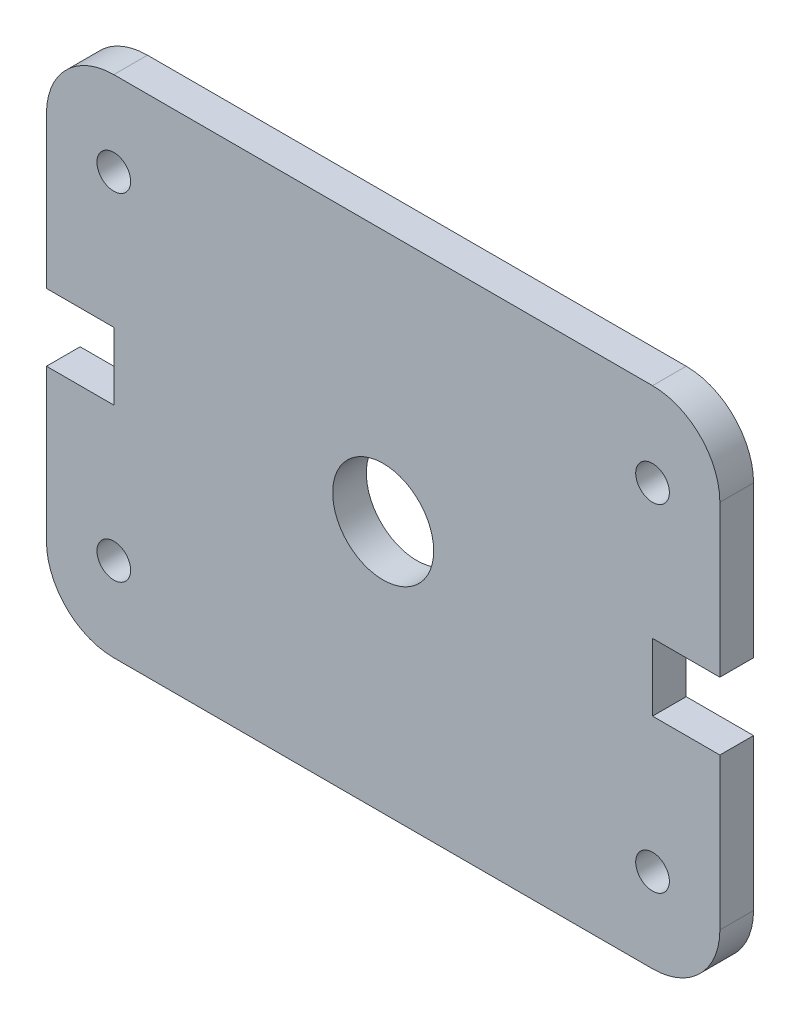
SolidWorks part; units mm, degrees
material "Plain Carbon Steel"
ref_plane "Front Plane" through (0, 0, 0) normal (0, 0, 1) x (1, 0, 0)
ref_plane "Top Plane" through (0, 0, 0) normal (0, 1, 0) x (1, 0, 0)
ref_plane "Right Plane" through (0, 0, 0) normal (1, 0, 0) x (0, 0, -1)
sketch "Sketch1" plane through (0, 0, 0) normal (0, 0, 1) x (1, 0, 0)
  line L1 (-40, -37.5) -> (40, -37.5)
  line L2 (-50, -27.5) -> (-50, 27.5)
  line L3 (-40, 37.5) -> (40, 37.5)
  line L4 (50, -27.5) -> (50, 27.5)
  line L5 (-50, -37.5) -> (50, 37.5) construction
  line L6 (-50, 37.5) -> (50, -37.5) construction
  arc A1 (40, 37.5) -> (50, 27.5) centre (40, 27.5) cw
  arc A2 (50, -27.5) -> (40, -37.5) centre (40, -27.5) cw
  arc A3 (-40, -37.5) -> (-50, -27.5) centre (-40, -27.5) cw
  arc A4 (-40, 37.5) -> (-50, 27.5) centre (-40, 27.5) ccw
  point P0 (0, 0)
  dimension "D4" = 10
  dimension "D1" = 100
  dimension "D2" = 75
extrude "Boss-Extrude1" add sketch "Sketch1" along normal mid plane 5
sketch "Sketch2" plane through (0, 0, 2.5) normal (0, 0, 1) x (1, 0, 0)
  line L0 (50, -27.5) -> (50, 27.5) construction
  line L1 (-50, 27.5) -> (-50, -27.5) construction
  line L2 (40, 37.5) -> (-40, 37.5) construction
  circle A0 centre (40, 25) radius 2.5
  circle A1 centre (-40, 25) radius 2.5
  circle A2 centre (-40, -25) radius 2.5
  circle A3 centre (40, -25) radius 2.5
  circle A5 centre (0, 0) radius 7.5
  point P0 (0, 0)
  dimension "D3" = 5
  dimension "D8" = 15
  dimension "D1" = 80
  dimension "D2" = 50
  dimension "D4" = 10
  dimension "D5" = 10
  dimension "D6" = 12.5
extrude "Cut-Extrude1" cut sketch "Sketch2" against normal through all
sketch "Sketch3" plane through (0, 0, 2.5) normal (0, 0, 1) x (1, 0, 0)
  circle A0 centre (0, 0) radius 12.5
  dimension "D1" = 25
sketch "Sketch4" plane through (0, 0, -2.5) normal (0, 0, -1) x (-1, 0, 0)
  line L0 (50, 27.5) -> (50, -27.5) construction
  line L1 (50, 5) -> (40, 5)
  line L2 (50, 5) -> (50, -5)
  line L3 (50, -5) -> (40, -5)
  line L4 (40, 5) -> (40, -5)
  line L5 (-50, -27.5) -> (-50, 27.5) construction
  line L6 (-50, 5) -> (-40, 5)
  line L7 (-50, 5) -> (-50, -5)
  line L8 (-50, -5) -> (-40, -5)
  line L9 (-40, 5) -> (-40, -5)
  point P6 (40, 0)
  point P14 (-40, 0)
  dimension "D1" = 10
  dimension "D2" = 10
extrude "Cut-Extrude3" cut sketch "Sketch4" against normal blind 10
